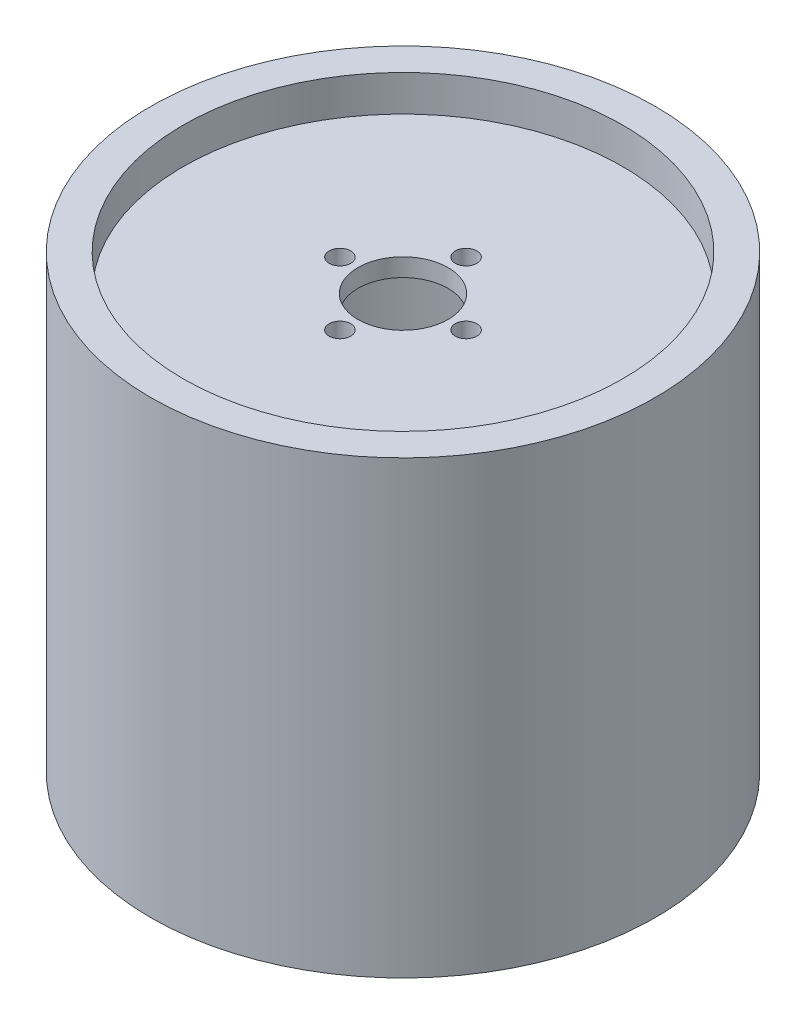
SolidWorks part; units mm, degrees
ref_plane "정면" through (0, 0, 0) normal (0, 0, 1) x (1, 0, 0)
ref_plane "윗면" through (0, 0, 0) normal (0, 1, 0) x (1, 0, 0)
ref_plane "우측면" through (0, 0, 0) normal (1, 0, 0) x (0, 0, -1)
sketch "스케치1" plane through (0, 0, 0) normal (0, 1, 0) x (1, 0, 0)
  circle A0 centre (0, 0) radius 70
  dimension "D1" = 140
extrude "보스-돌출1" add sketch "스케치1" along normal blind 125 contours A0
sketch "스케치4" plane through (0, 0, 0) normal (0, -1, 0) x (1, 0, 0)
  circle A0 centre (0, 0) radius 60
  dimension "D1" = 120
extrude "컷-돌출4" cut sketch "스케치4" against normal blind 110
sketch "스케치5" plane through (0, 125, 0) normal (0, 1, 0) x (1, 0, 0)
  circle A0 centre (0, 0) radius 61
  dimension "D1" = 122
extrude "컷-돌출5" cut sketch "스케치5" against normal blind 10
sketch "스케치6" plane through (0, 115, 0) normal (0, 1, 0) x (1, 0, 0)
  circle A0 centre (0, 0) radius 12.5
  circle A1 centre (0, -17.5) radius 3
  circle A2 centre (-17.5, 0) radius 3
  circle A3 centre (0, 17.5) radius 3
  circle A4 centre (17.5, 0) radius 3
  point P14 (0, 0)
  dimension "D1" = 25
  dimension "D2" = 4
extrude "컷-돌출6" cut sketch "스케치6" against normal through all
sketch "스케치7" plane through (0, 0, 0) normal (0, -1, 0) x (1, 0, 0)
  circle A0 centre (0, 0) radius 60
  circle A1 centre (0, 0) radius 50
  dimension "D1" = 100
extrude "보스-돌출2" add sketch "스케치7" against normal blind 5
sketch "스케치8" plane through (0, 0, 0) normal (0, -1, 0) x (1, 0, 0)
  circle A1 centre (0, -55) radius 2.5
  circle A2 centre (-55, 0) radius 2.5
  circle A3 centre (0, 55) radius 2.5
  circle A4 centre (55, 0) radius 2.5
  point P15 (0, 0)
  dimension "D2" = 4
extrude "컷-돌출7" cut sketch "스케치8" against normal blind 5
sketch "스케치9" plane through (0, 0, 0) normal (0, -1, 0) x (1, 0, 0)
  circle A0 centre (0, 0) radius 7.5
  dimension "D1" = 15
